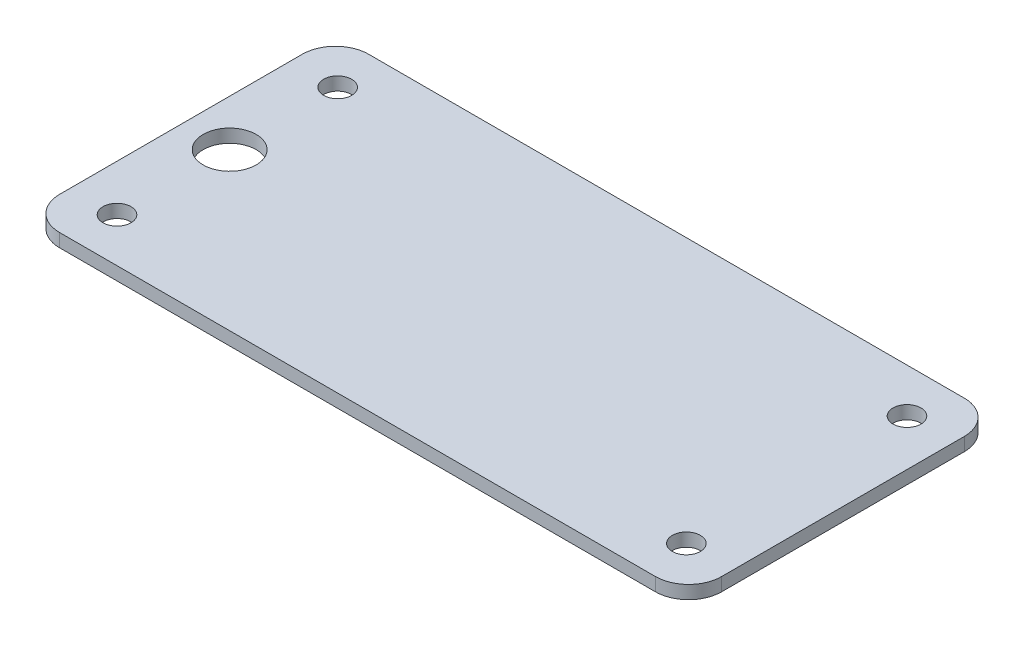
SolidWorks part; units mm, degrees
ref_plane "Front" through (0, 0, 0) normal (0, 0, 1) x (1, 0, 0)
ref_plane "Top" through (0, 0, 0) normal (0, 1, 0) x (1, 0, 0)
ref_plane "Right" through (0, 0, 0) normal (1, 0, 0) x (0, 0, -1)
sketch "Esboço2" plane through (0, 0, 0) normal (0, 1, 0) x (1, 0, 0)
  line L1 (0, 0) -> (150, 0)
  line L2 (0, 0) -> (0, 70)
  line L3 (0, 70) -> (150, 70)
  line L4 (150, 0) -> (150, 70)
extrude "Ressalto-extrusão1" add sketch "Esboço2" along normal blind 3
sketch "Esboço4" plane through (0, 3, 0) normal (0, 1, 0) x (1, 0, 0)
  line L0 (0, 70) -> (10.5, 70)
  line L1 (150, 70) -> (0, 70) construction
  line L2 (10.5, 70) -> (10.5, 60)
  line L3 (150, 70) -> (139.5, 70)
  line L4 (139.5, 70) -> (139.5, 60)
  line L5 (10.5, 0) -> (10.5, 10)
  line L6 (0, 0) -> (150, 0) construction
  line L7 (139.5, 0) -> (139.5, 10)
  circle A0 centre (10.5, 60) radius 3.175
  circle A1 centre (139.5, 60) radius 3.175
  circle A2 centre (139.5, 10) radius 3.175
  circle A3 centre (10.5, 10) radius 3.175
  dimension "D1" = 2
  dimension "D3" = 50
  dimension "D4" = 129
  dimension "D2" = 2
extrude "Corte-extrusão1" cut sketch "Esboço4" against normal blind 3
fillet "Filete1" radius 7.5 4 edges at (0, 1.5, 0) (150, 1.5, 0) (150, 1.5, -70) (0, 1.5, -70)
sketch "Esboço6" plane through (0, 3, 0) normal (0, 1, 0) x (1, 0, 0)
  circle A0 centre (10.5, 35.527) radius 6
extrude "Corte-extrusão2" cut sketch "Esboço6" against normal blind 10
